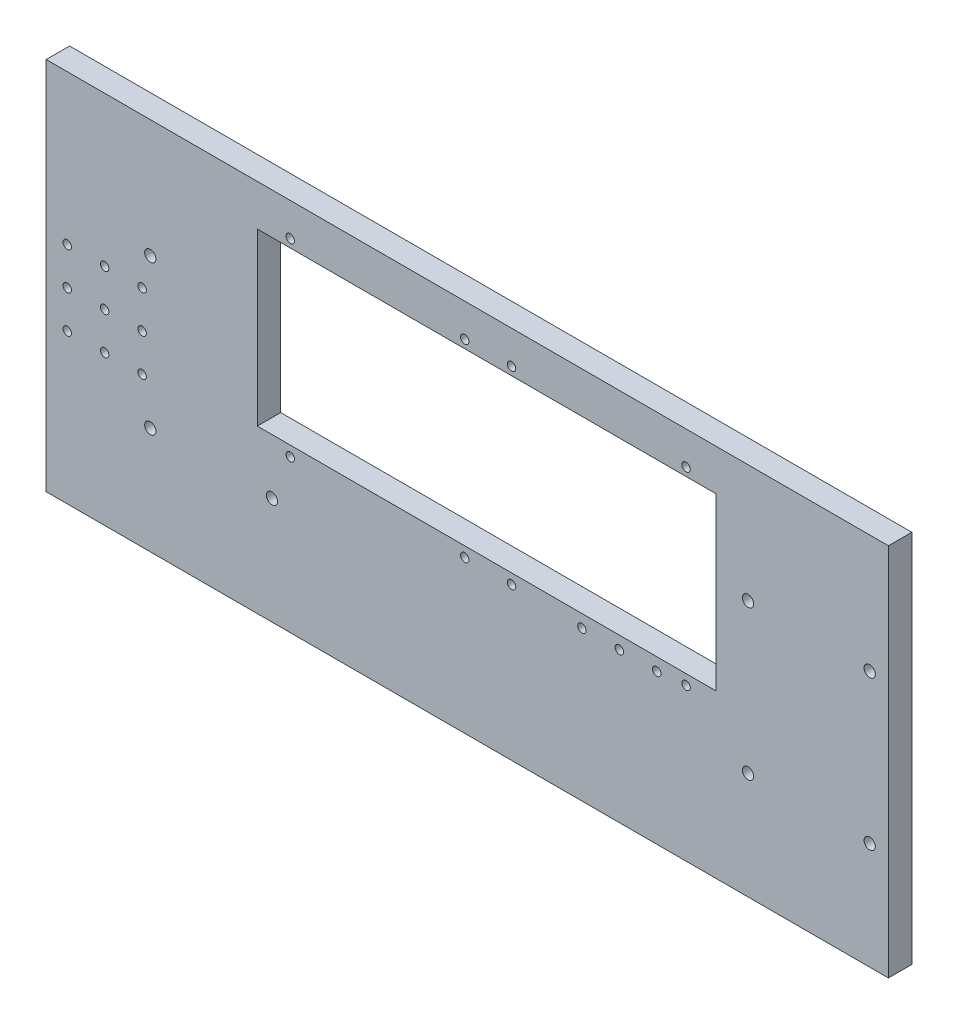
SolidWorks part; units mm, degrees
ref_plane "Plan de face" through (0, 0, 0) normal (0, 0, 1) x (1, 0, 0)
ref_plane "Plan de dessus" through (0, 0, 0) normal (0, 1, 0) x (1, 0, 0)
ref_plane "Plan de droite" through (0, 0, 0) normal (1, 0, 0) x (0, 0, -1)
sketch "Esquisse1" plane through (0, 0, 0) normal (0, 0, 1) x (1, 0, 0)
  line L1 (-90, -40) -> (90, -40)
  line L2 (-90, -40) -> (-90, 40)
  line L3 (-90, 40) -> (90, 40)
  line L4 (90, -40) -> (90, 40)
  line L5 (-90, -40) -> (90, 40) construction
  line L6 (-90, 40) -> (90, -40) construction
  point P0 (0, 0)
  dimension "D1" = 180
  dimension "D2" = 80
extrude "Boss.-Extru.1" add sketch "Esquisse1" along normal blind 5
sketch "Esquisse2" plane through (0, 0, 0) normal (0, 0, -1) x (-1, 0, 0)
  line L0 (-46.7564, 32.9518) -> (83.9006, 32.9518) construction
  circle A0 centre (-46.7564, 32.9518) radius 0.9
  circle A1 centre (-9.4564, 32.9518) radius 0.9
  circle A2 centre (0.5436, 32.9518) radius 0.9
  circle A3 centre (37.8436, 32.9518) radius 0.9
  circle A4 centre (-46.7564, 12.7518) radius 0.9
  circle A5 centre (-9.4564, 12.7518) radius 0.9
  circle A6 centre (0.5436, 12.7518) radius 0.9
  circle A7 centre (37.8436, 12.7518) radius 0.9
  circle A8 centre (-46.7564, -7.4482) radius 0.9
  circle A9 centre (-9.4564, -7.4482) radius 0.9
  circle A10 centre (0.5436, -7.4482) radius 0.9
  circle A11 centre (37.8436, -7.4482) radius 0.9
  dimension "D1" = 2
  dimension "D2" = 10
  dimension "D3" = 2
  dimension "D4" = 3
extrude "Enlèv. mat.-Extru.1" cut sketch "Esquisse2" against normal blind 5
sketch "Esquisse4" plane through (0, 0, 0) normal (0, 0, -1) x (-1, 0, 0)
  line L0 (-90, 0) -> (90, 0) construction
  line L1 (-90, -40) -> (-90, 40) construction
  line L2 (90, 40) -> (90, -40) construction
  circle A0 centre (85.5, 0) radius 0.9
  circle A1 centre (77.5, 0) radius 0.9
  circle A2 centre (69.5, 0) radius 0.9
  circle A3 centre (77.5, 8) radius 0.9
  circle A4 centre (69.5, 8) radius 0.9
  circle A5 centre (85.5, 8) radius 0.9
  circle A6 centre (69.5, -8) radius 0.9
  circle A7 centre (77.5, -8) radius 0.9
  circle A8 centre (85.5, -8) radius 0.9
  circle A9 centre (-24.5, 0) radius 0.9
  circle A10 centre (-32.5, 0) radius 0.9
  circle A11 centre (-40.5, 0) radius 0.9
  circle A12 centre (-32.5, 8) radius 0.9
  circle A13 centre (-40.5, 8) radius 0.9
  circle A14 centre (-24.5, 8) radius 0.9
  circle A15 centre (-40.5, -8) radius 0.9
  circle A16 centre (-32.5, -8) radius 0.9
  circle A17 centre (-24.5, -8) radius 0.9
  dimension "D1" = 4.5
  dimension "D2" = 3
  dimension "D3" = 2
  dimension "D4" = 2
  dimension "D5" = 2
extrude "Enlèv. mat.-Extru.2" cut sketch "Esquisse4" against normal through all
sketch "Esquisse5" plane through (0, 0, 0) normal (0, 0, -1) x (-1, 0, 0)
  line L0 (-90, 0) -> (90, 0) construction
  line L1 (-90, -40) -> (-90, 40) construction
  line L2 (90, -17) -> (90, 17) construction
  line L3 (-60, 14.8) -> (-60, -17.1) construction
  line L4 (-86, 14.8) -> (-86, -17.1) construction
  circle A0 centre (-60, 14.8) radius 1.2
  circle A2 centre (-86, 14.8) radius 1.2
  circle A3 centre (-86, -17.1) radius 1.2
  circle A4 centre (-60, -17.1) radius 1.2
  circle A5 centre (67.75, 14.8) radius 1.2
  circle A6 centre (41.75, 14.8) radius 1.2
  circle A7 centre (41.75, -17.1) radius 1.2
  circle A8 centre (67.75, -17.1) radius 1.2
  dimension "D1" = 14.8
  dimension "D4" = 17.1
  dimension "D2" = 30
  dimension "D5" = 17.1
  dimension "D7" = 26
  dimension "D3" = 2
  dimension "D6" = 2
extrude "Enlèv. mat.-Extru.3" cut sketch "Esquisse5" against normal through all
sketch "Esquisse6" plane through (0, 0, 0) normal (0, 0, -1) x (-1, 0, 0)
  line L1 (-53.1696, 31.1939) -> (44.8735, 31.1939)
  line L2 (-53.1696, 31.1939) -> (-53.1696, -5.2836)
  line L3 (-53.1696, -5.2836) -> (44.8735, -5.2836)
  line L4 (44.8735, 31.1939) -> (44.8735, -5.2836)
extrude "Enlèv. mat.-Extru.4" cut sketch "Esquisse6" against normal through all
